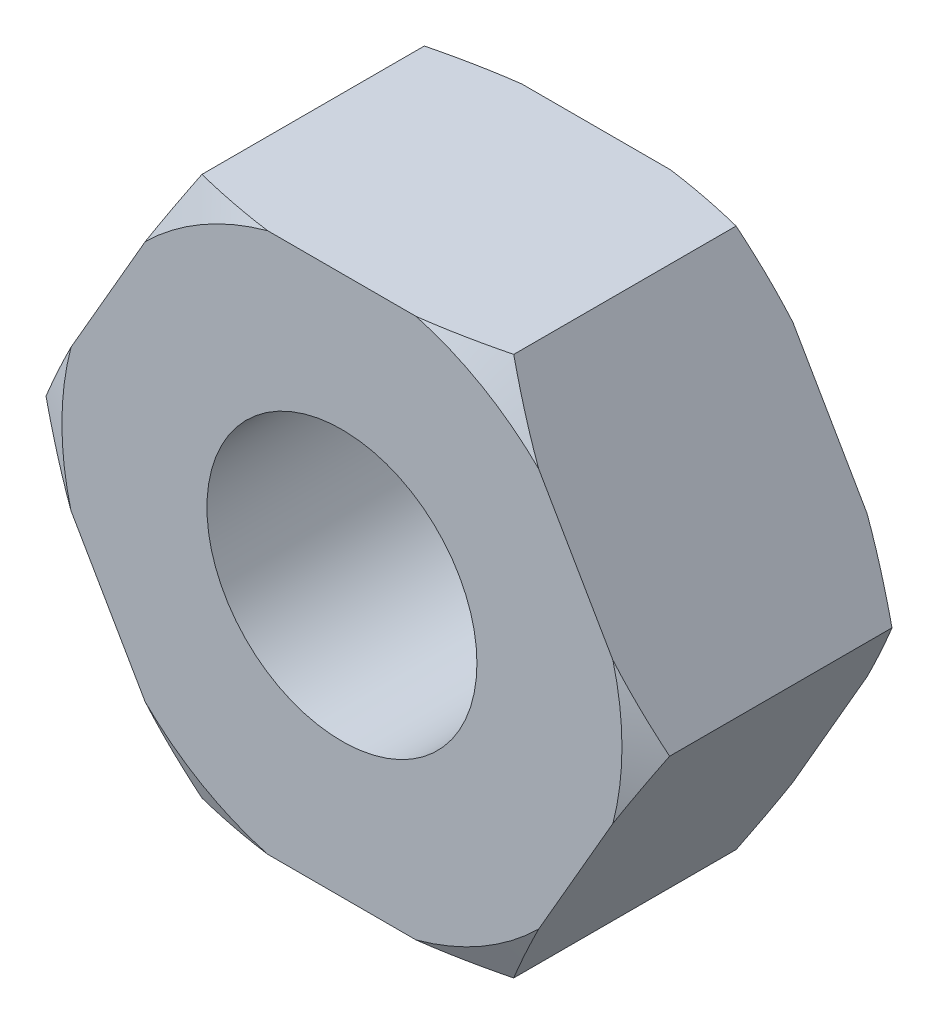
SolidWorks part; units mm, degrees
material "1.0037 (S235JR)"
ref_plane "Ön Düzlem" through (0, 0, 0) normal (0, 0, 1) x (1, 0, 0)
ref_plane "Üst Düzlem" through (0, 0, 0) normal (0, 1, 0) x (1, 0, 0)
ref_plane "Sağ Düzlem" through (0, 0, 0) normal (1, 0, 0) x (0, 0, -1)
sketch "Çizim1" plane through (0, 0, 0) normal (0, 0, 1) x (1, 0, 0)
  line L1 (9.815, 0) -> (4.9075, 8.5)
  line L2 (4.9075, 8.5) -> (-4.9075, 8.5)
  line L3 (-4.9075, 8.5) -> (-9.815, 0)
  line L4 (-9.815, 0) -> (-4.9075, -8.5)
  line L5 (-4.9075, -8.5) -> (4.9075, -8.5)
  line L6 (4.9075, -8.5) -> (9.815, 0)
  circle A0 centre (0, 0) radius 8.5 construction
  circle A1 centre (0, 0) radius 4.25
  dimension "D1" = 8.5
  dimension "D2" = 17
extrude "Yükseklik-Ekstrüzyon1" add sketch "Çizim1" along normal blind 8
cosmetic thread "Kozmetik Diş Açma1" parameters "D2"=10
sketch "Çizim2" plane through (0, 0, 0) normal (0, 1, 0) x (1, 0, 0)
  line L0 (-9.815, 0) -> (-8.815, 0)
  line L1 (-4.9075, 0) -> (-9.815, 0) construction
  line L2 (-8.815, 0) -> (-9.815, -0.5)
  line L3 (-9.815, -8) -> (-9.815, 0) construction
  line L4 (-9.815, -0.5) -> (-9.815, 0)
  line L5 (-9.815, -8) -> (-9.815, -7.5)
  line L6 (-9.815, -7.5) -> (-8.815, -8)
  line L7 (-4.9075, -8) -> (-9.815, -8) construction
  line L8 (-8.815, -8) -> (-9.815, -8)
  line L9 (0, 0) -> (0, -8) construction
  line L10 (4.9075, -8) -> (-4.9075, -8) construction
  dimension "D1" = 0.5
  dimension "D2" = 1
  dimension "D3" = 0.5
  dimension "D4" = 1
revolve "Kes-Döndür1" cut sketch "Çizim2" angle 360 about L9
